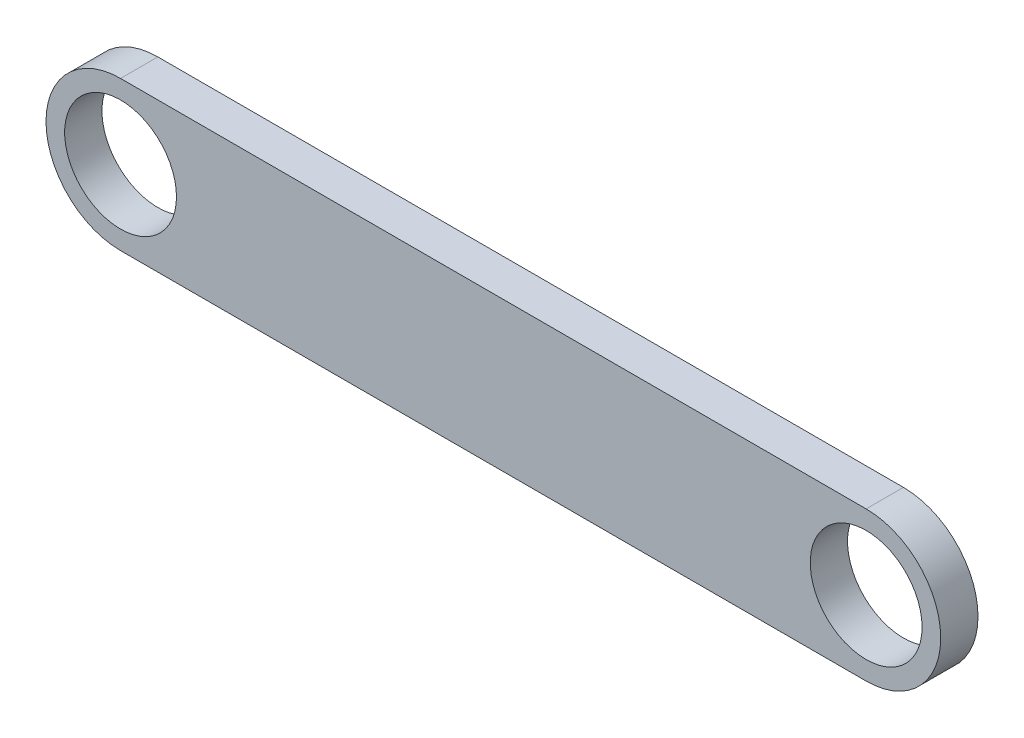
SolidWorks part; units mm, degrees
ref_plane "Front Plane" through (0, 0, 0) normal (0, 0, 1) x (1, 0, 0)
ref_plane "Top Plane" through (0, 0, 0) normal (0, 1, 0) x (1, 0, 0)
ref_plane "Right Plane" through (0, 0, 0) normal (1, 0, 0) x (0, 0, -1)
sketch "Sketch1" plane through (0, 0, 0) normal (0, 0, 1) x (1, 0, 0)
  line L0 (-25.1567, 2.2615) -> (-5.1567, 2.2615) construction
  line L1 (-25.1567, 4.2615) -> (-5.1567, 4.2615)
  line L2 (-25.1567, 0.2615) -> (-5.1567, 0.2615)
  arc A0 (-25.1567, 4.2615) -> (-25.1567, 0.2615) centre (-25.1567, 2.2615) ccw
  arc A1 (-5.1567, 0.2615) -> (-5.1567, 4.2615) centre (-5.1567, 2.2615) ccw
  circle A2 centre (-25.1567, 2.2615) radius 1.5
  circle A3 centre (-5.1567, 2.2615) radius 1.5
  point P2 (-15.1567, 2.2615)
extrude "Boss-Extrude1" add sketch "Sketch1" along normal blind 1
